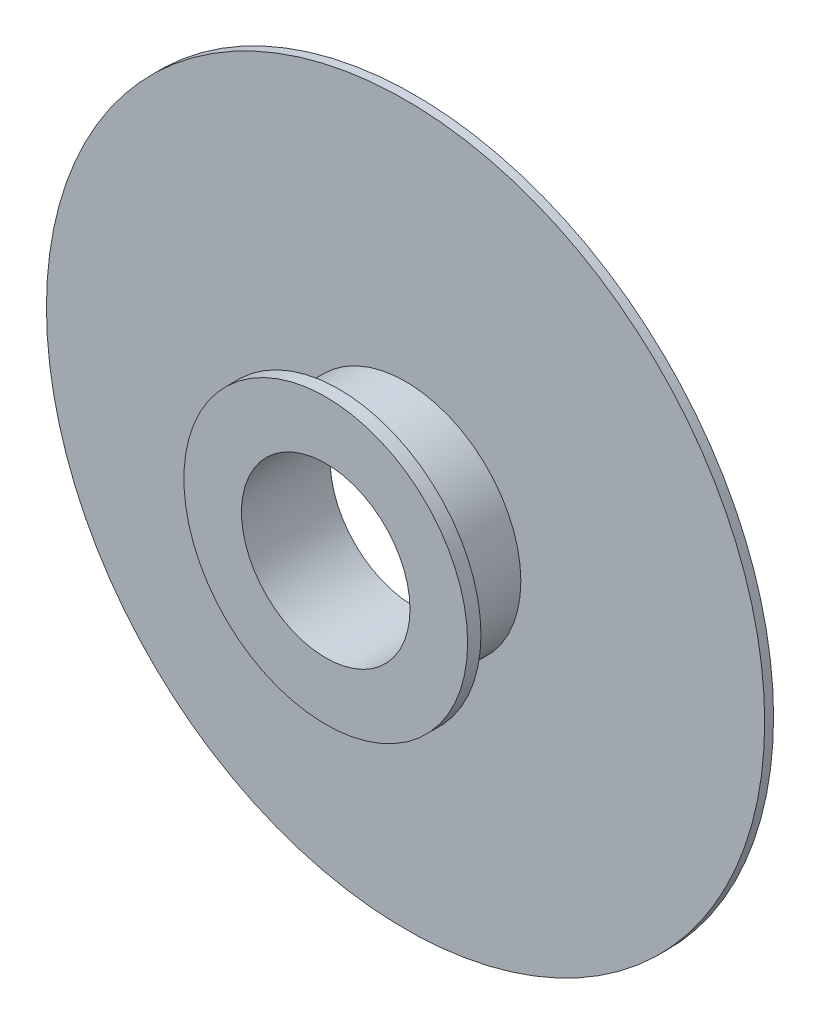
SolidWorks part; units mm, degrees
ref_plane "Front Plane" through (0, 0, 0) normal (0, 0, 1) x (1, 0, 0)
ref_plane "Top Plane" through (0, 0, 0) normal (0, 1, 0) x (1, 0, 0)
ref_plane "Right Plane" through (0, 0, 0) normal (1, 0, 0) x (0, 0, -1)
sketch "Sketch1" plane through (0, 0, 0) normal (0, 0, 1) x (1, 0, 0)
  circle A0 centre (0, 0) radius 81
  circle A1 centre (0, 0) radius 19
  dimension "D1" = 162
  dimension "D2" = 38
extrude "Boss-Extrude1" add sketch "Sketch1" along normal blind 2
sketch "Sketch2" plane through (0, 0, 2) normal (0, 0, 1) x (1, 0, 0)
  circle A0 centre (0, 0) radius 19 construction
  circle A1 centre (0, 0) radius 19
  circle A2 centre (0, 0) radius 26
  dimension "D1" = 7
extrude "Boss-Extrude2" add sketch "Sketch2" along normal blind 18
sketch "Sketch3" plane through (0, 0, 20) normal (0, 0, 1) x (1, 0, 0)
  circle A0 centre (0, 0) radius 26 construction
  circle A1 centre (0, 0) radius 26
  circle A2 centre (0, 0) radius 32
  dimension "D1" = 6
extrude "Boss-Extrude3" add sketch "Sketch3" against normal blind 3
